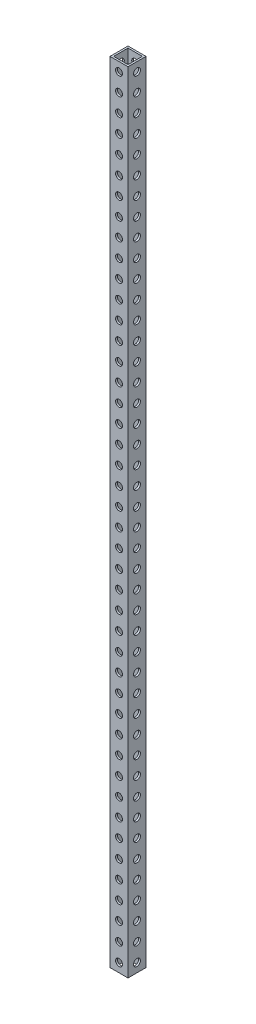
SolidWorks part; units mm, degrees
ref_plane "Front Plane" through (0, 0, 0) normal (0, 0, 1) x (1, 0, 0)
ref_plane "Top Plane" through (0, 0, 0) normal (0, 1, 0) x (1, 0, 0)
ref_plane "Right Plane" through (0, 0, 0) normal (1, 0, 0) x (0, 0, -1)
sketch "Sketch1" plane through (0, 0, 0) normal (1, 0, 0) x (0, 0, -1)
  line L0 (0, -558.8) -> (0, 558.8)
  dimension "D1" = 1117.6
other "Rectangular tube 1IN X 1IN(1)"
ref_plane "Plane1" through (-12.7, -558.8, -12.7) normal (0, 1, 0) x (0, 0, 1)
sketch "Sketch12" plane through (-12.7, -558.8, -12.7) normal (0, 1, 0) x (0, 0, 1)
  line L0 (0, 0) -> (0, 25.4)
  line L1 (0, 25.4) -> (25.4, 25.4)
  line L2 (0, 0) -> (25.4, 0)
  line L3 (25.4, 25.4) -> (25.4, 0)
  line L4 (2.54, 22.86) -> (22.86, 22.86)
  line L5 (22.86, 22.86) -> (22.86, 2.54)
  line L6 (2.54, 2.54) -> (22.86, 2.54)
  line L7 (2.54, 2.54) -> (2.54, 22.86)
  line L8 (0, 0) -> (25.4, 25.4) construction
  point P0 (0, 0)
  point P2 (0, 12.7)
  point P4 (0, 0)
  point P6 (12.7, 0)
  point P7 (0, 12.7)
  point P8 (25.4, 12.7)
  point P9 (25.4, 0)
  point P10 (12.7, 25.4)
  point P11 (25.4, 25.4)
  point P12 (0, 25.4)
  point P16 (0, 0)
  point P17 (0, 0)
  point P19 (12.7, 12.7)
  point P20 (25.4, 0)
  point P23 (25.4, 25.4)
  point P26 (0, 25.4)
  dimension "D2" = 25.4
  dimension "D3" = 2.54
  dimension "D1" = 25.4
hole_wizard "3/8 Clearance Hole1" positions "Sketch15" profile "Sketch16" hole size "3/8" standard "ANSI Inch" end condition through all
sketch "Sketch15" plane through (-12.7, 0, 0) normal (-1, 0, 0) x (0, 0, 1)
  line L0 (0, 558.8) -> (0, 546.1) construction
  line L1 (-12.7, 558.8) -> (12.7, 558.8) construction
  point P0 (0, 546.1)
  point P22 (0, 520.7)
  point P23 (0, 495.3)
  point P24 (0, 469.9)
  point P25 (0, 444.5)
  point P26 (0, 419.1)
  point P27 (0, 393.7)
  point P28 (0, 368.3)
  point P29 (0, 342.9)
  point P30 (0, 317.5)
  point P31 (0, 292.1)
  point P32 (0, 266.7)
  point P33 (0, 241.3)
  point P34 (0, 215.9)
  point P35 (0, 190.5)
  point P36 (0, 165.1)
  point P37 (0, 139.7)
  point P38 (0, 114.3)
  point P39 (0, 88.9)
  point P40 (0, 63.5)
  point P41 (0, 38.1)
  point P42 (0, 12.7)
  point P43 (0, -12.7)
  point P44 (0, -38.1)
  point P45 (0, -63.5)
  point P46 (0, -88.9)
  point P47 (0, -114.3)
  point P48 (0, -139.7)
  point P49 (0, -165.1)
  point P50 (0, -190.5)
  point P51 (0, -215.9)
  point P52 (0, -241.3)
  point P53 (0, -266.7)
  point P54 (0, -292.1)
  point P55 (0, -317.5)
  point P56 (0, -342.9)
  point P57 (0, -368.3)
  point P58 (0, -393.7)
  point P59 (0, -419.1)
  point P60 (0, -444.5)
  point P61 (0, -469.9)
  point P62 (0, -495.3)
  point P63 (0, -520.7)
  point P64 (0, -546.1)
  point P65 (0, -571.5)
  point P66 (0, -596.9)
  point P67 (0, -622.3)
  point P68 (0, -647.7)
  dimension "D1" = 12.7
  dimension "D2" = 48
sketch "Sketch16" plane through (-12.7, 546.1, 0) normal (0, 1, 0) x (0, 0, 1)
  line L0 (0, 0) -> (0, 25.4)
  line L1 (0, 25.4) -> (4.9022, 25.4)
  line L2 (4.9022, 25.4) -> (4.9022, 0)
  line L5 (4.9022, 0) -> (0, 0)
  line L11 (0, -6.35) -> (0, 107.95) construction
  dimension "Thru Hole Dia." = 9.8044
  dimension "Thru Hole Depth" = 25.4
hole_wizard "3/8 Clearance Hole2" positions "Sketch18" profile "Sketch19" hole size "3/8" standard "ANSI Inch" end condition through all
sketch "Sketch18" plane through (0, 0, 12.7) normal (0, 0, 1) x (1, 0, 0)
  line L0 (0, 558.8) -> (0, 546.1) construction
  line L1 (-12.7, 558.8) -> (12.7, 558.8) construction
  point P0 (0, 546.1)
  point P14 (0, 520.7)
  point P15 (0, 495.3)
  point P16 (0, 469.9)
  point P17 (0, 444.5)
  point P18 (0, 419.1)
  point P19 (0, 393.7)
  point P20 (0, 368.3)
  point P21 (0, 342.9)
  point P22 (0, 317.5)
  point P23 (0, 292.1)
  point P24 (0, 266.7)
  point P25 (0, 241.3)
  point P26 (0, 215.9)
  point P27 (0, 190.5)
  point P28 (0, 165.1)
  point P29 (0, 139.7)
  point P30 (0, 114.3)
  point P31 (0, 88.9)
  point P32 (0, 63.5)
  point P33 (0, 38.1)
  point P34 (0, 12.7)
  point P35 (0, -12.7)
  point P36 (0, -38.1)
  point P37 (0, -63.5)
  point P38 (0, -88.9)
  point P39 (0, -114.3)
  point P40 (0, -139.7)
  point P41 (0, -165.1)
  point P42 (0, -190.5)
  point P43 (0, -215.9)
  point P44 (0, -241.3)
  point P45 (0, -266.7)
  point P46 (0, -292.1)
  point P47 (0, -317.5)
  point P48 (0, -342.9)
  point P49 (0, -368.3)
  point P50 (0, -393.7)
  point P51 (0, -419.1)
  point P52 (0, -444.5)
  point P53 (0, -469.9)
  point P54 (0, -495.3)
  point P55 (0, -520.7)
  point P56 (0, -546.1)
  point P57 (0, -571.5)
  point P58 (0, -596.9)
  point P59 (0, -622.3)
  point P60 (0, -647.7)
  dimension "D1" = 12.7
  dimension "D2" = 48
sketch "Sketch19" plane through (0, 546.1, 12.7) normal (1, 0, 0) x (0, -1, 0)
  line L0 (0, 0) -> (0, 25.4)
  line L1 (0, 25.4) -> (4.9022, 25.4)
  line L2 (4.9022, 25.4) -> (4.9022, 0)
  line L5 (4.9022, 0) -> (0, 0)
  line L11 (0, -6.35) -> (0, 107.95) construction
  dimension "Thru Hole Dia." = 9.8044
  dimension "Thru Hole Depth" = 25.4
